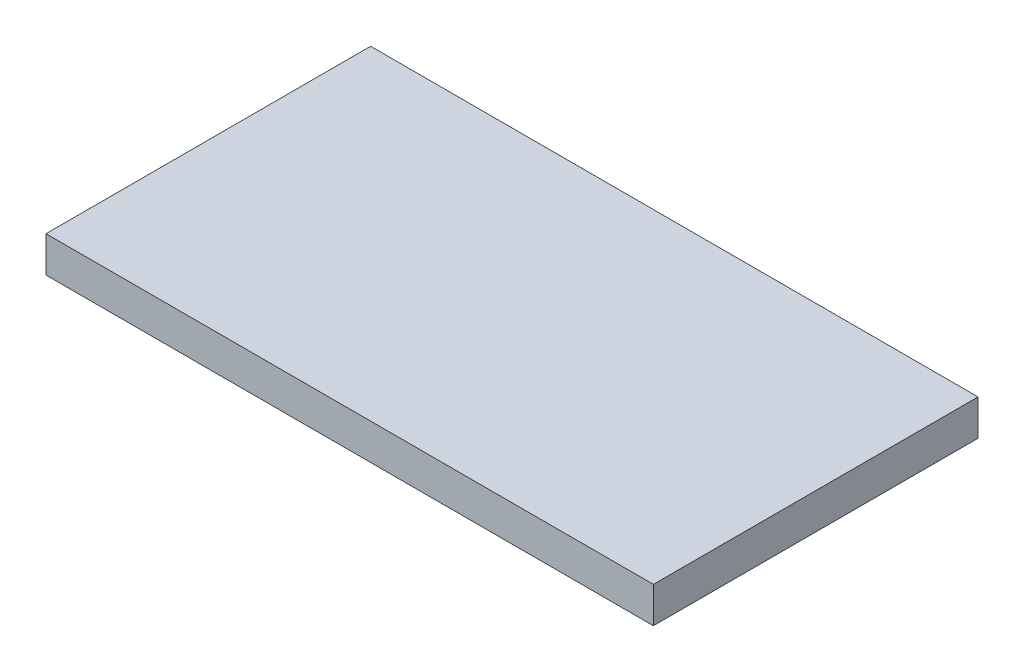
SolidWorks part; units mm, degrees
ref_plane "Front Plane" through (0, 0, 0) normal (0, 0, 1) x (1, 0, 0)
ref_plane "Top Plane" through (0, 0, 0) normal (0, 1, 0) x (1, 0, 0)
ref_plane "Right Plane" through (0, 0, 0) normal (1, 0, 0) x (0, 0, -1)
sketch "Sketch1" plane through (0, 0, 0) normal (0, 1, 0) x (1, 0, 0)
  line L1 (-21.5319, -11.5085) -> (21.5319, -11.5085)
  line L2 (-21.5319, -11.5085) -> (-21.5319, 11.5085)
  line L3 (-21.5319, 11.5085) -> (21.5319, 11.5085)
  line L4 (21.5319, -11.5085) -> (21.5319, 11.5085)
  line L5 (-21.5319, -11.5085) -> (21.5319, 11.5085) construction
  line L6 (-21.5319, 11.5085) -> (21.5319, -11.5085) construction
  point P0 (0, 0)
extrude "Boss-Extrude1" add sketch "Sketch1" along normal blind 2.54
